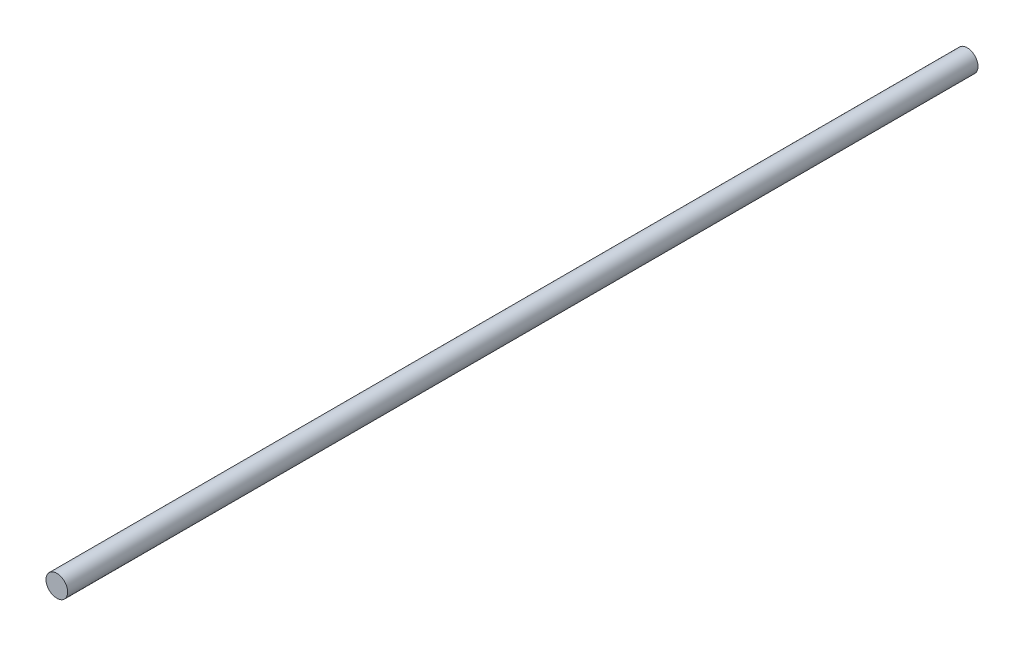
SolidWorks part; units mm, degrees
ref_plane "Plan de face" through (0, 0, 0) normal (0, 0, 1) x (1, 0, 0)
ref_plane "Plan de dessus" through (0, 0, 0) normal (0, 1, 0) x (1, 0, 0)
ref_plane "Plan de droite" through (0, 0, 0) normal (1, 0, 0) x (0, 0, -1)
sketch "Esquisse1" plane through (0, 0, 0) normal (0, 0, 1) x (1, 0, 0)
  circle A0 centre (0, 0) radius 4
  dimension "D1" = 8
extrude "Boss.-Extru.1" add sketch "Esquisse1" along normal blind 336
